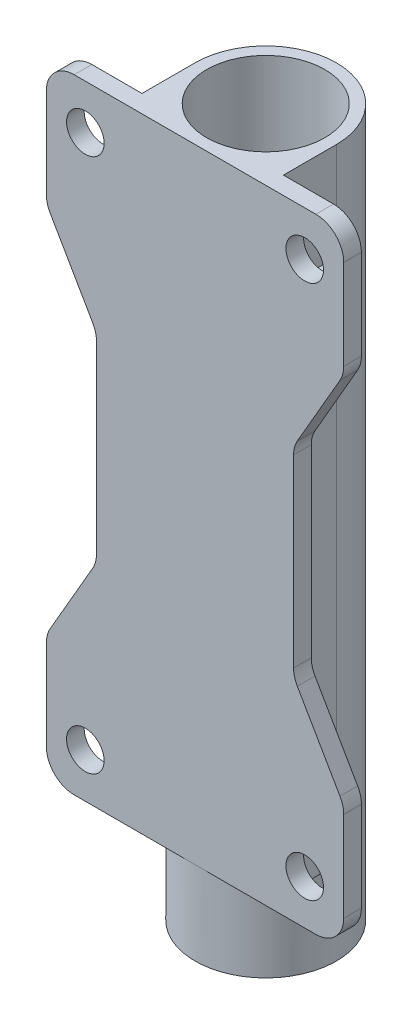
SolidWorks part; units mm, degrees
other "pipe" parameters "D1"=877.6559, "D2"=75.5022, "D3"=726.6514, "D4"=726.6514, "D5"=877.6559, "D6"=4.445, "D7"=9.9955, "\"bearing_bore_min\""=42.164, "D8"=59.5421, "D9"=6.35, "D10"=1.4503
material "6061 Alloy"
ref_plane "Front Plane" through (0, 0, 0) normal (0, 0, 1) x (1, 0, 0)
ref_plane "Top Plane" through (0, 0, 0) normal (0, 1, 0) x (1, 0, 0)
ref_plane "Right Plane" through (0, 0, 0) normal (1, 0, 0) x (0, 0, -1)
sketch "Sketch11" plane through (0, 0, 0) normal (0, 0, 1) x (1, 0, 0)
  line L0 (0, 0) -> (0, 109.6398) construction
  line L1 (0, 0) -> (-89.1372, 0) construction
sketch "Sketch12" plane through (0, 0, 0) normal (0, 0, 1) x (1, 0, 0)
  line L0 (-25.4, 0) -> (-25.4, 254)
  line L1 (200000, 0) -> (-200089.1372, 0) construction
  line L4 (-21.2287, 0) -> (-25.4, 0)
  line L5 (-21.2287, 0) -> (-21.2287, 127)
  line L9 (-21.2287, 127) -> (-21.2287, 254)
  line L10 (-21.2287, 254) -> (-25.4, 254)
  line L13 (-21.2287, 254) -> (0, 254) construction
  line L14 (0, 254) -> (0, 0) construction
  line L15 (0, 0) -> (-21.2287, 0) construction
  point P12 (-25.4, 0)
  dimension "D5" = 254
  dimension "D6" = 4.1713
  dimension "D1" = 50.8
  dimension "D2" = 42.4573
  dimension "D8" = 50.8
  dimension "D9" = 0
revolve "Revolve1" add sketch "Sketch12" angle 360 about L0
ref_plane "mideplane" through (0, 127, 0) normal (0, -1, 0) x (-1, 0, 0)
ref_plane "top pipe plane" through (0, 30, 0) normal (0, -1, 0) x (-1, 0, 0)
ref_plane "bottom pipe plane" through (0, 254, 0) normal (0, 1, 0) x (1, 0, 0)
ref_plane "pipe support midplane" through (0, 142, 0) normal (0, -1, 0) x (-1, 0, 0)
sketch "Sketch14" plane through (0, 30, 0) normal (0, -1, 0) x (-1, 0, 0)
  line L0 (0, 0) -> (-25.4, 0) construction
  line L1 (0, 0) -> (25.4, 0) construction
  line L7 (-25.4, -25.4) -> (25.4, -25.4)
  line L9 (25.4, -25.4) -> (25.4, 0)
  line L10 (-25.4, -25.4) -> (-25.4, 0)
  circle A0 centre (0, 0) radius 25.4 construction
  circle A1 centre (0, 0) radius 25.4
  circle A2 centre (0, 0) radius 25.4 construction
  arc A3 (25.4, 0) -> (-25.4, 0) centre (0, 0) cw
  dimension "D1" = 0
  dimension "D2" = 0
extrude "Boss-Extrude1" add sketch "Sketch14" against normal up to surface (224 mm away) contours A1 L10 L7 L9 | A1 L7 L9
sketch "Sketch27" plane through (0, 0, 25.4) normal (0, 0, 1) x (1, 0, 0)
  line L0 (25.4, 30) -> (53.4, 30)
  line L1 (53.4, 30) -> (53.4, 75)
  line L2 (53.4, 75) -> (35.4, 106.1769)
  line L3 (35.4, 106.1769) -> (35.4, 177.8231)
  line L4 (35.4, 177.8231) -> (53.4, 209)
  line L5 (25.4, 30) -> (25.4, 254)
  line L6 (25.4, 254) -> (-25.4, 254)
  line L7 (-25.4, 254) -> (-25.4, 30)
  line L8 (-25.4, 30) -> (0, 30)
  line L9 (0, 30) -> (25.4, 30)
  line L10 (25.4, 30) -> (25.4, 254) construction
  line L11 (25.4, 254) -> (-25.4, 254)
  line L12 (-25.4, 254) -> (-25.4, 30)
  line L13 (-25.4, 30) -> (0, 30)
  line L14 (0, 30) -> (25.4, 30)
  line L15 (53.4, 209) -> (53.4, 254)
  line L16 (25.4, 254) -> (53.4, 254)
  line L17 (25.4, 254) -> (25.4, 30) construction
  line L18 (25.4, 62) -> (53.4, 30) construction
  line L20 (25.4, 222) -> (53.4, 254) construction
  circle A0 centre (39.4, 46) radius 6 construction
  point P14 (39.4, 238)
  dimension "D2" = 12
  dimension "D3" = 10
  dimension "D6" = 8
  dimension "D4" = 10
  dimension "D5" = 45
  dimension "D7" = 30
  dimension "D1" = 0
extrude "Boss-Extrude2" add sketch "Sketch27" against normal blind 6.35
ref_plane "Plane1" through (0, 65, 0) normal (0, -1, 0) x (-1, 0, 0)
sketch "Sketch32" plane through (0, 65, 0) normal (0, -1, 0) x (-1, 0, 0)
  line L0 (-25.4, -19.05) -> (-53.4, -19.05) construction
  line L1 (-25.4, -19.05) -> (-53.4, -19.05)
  line L3 (-25.4, 0) -> (-25.4, -19.05)
  line L6 (-53.4, -19.05) -> (-25.4, 0)
  arc A0 (25.4, 0) -> (-25.4, 0) centre (0, 0) ccw construction
  arc A1 (25.4, 0) -> (-25.4, 0) centre (0, 0) ccw
extrude "Boss-Extrude3" add sketch "Sketch32" against normal blind 5
mirror "Mirror2" about plane through (0, 142, 0) normal (0, -1, 0) of "Boss-Extrude3"
hole_wizard "M12 Clearance Hole1" positions "Sketch28" profile "Sketch29" hole size "M12" standard "ISO" end condition through all
sketch "Sketch28" plane through (0, 0, 25.4) normal (0, 0, 1) x (1, 0, 0)
  point P0 (39.4, 46)
  point P3 (39.4, 238)
sketch "Sketch29" plane through (39.4, 46, 25.4) normal (1, 0, 0) x (0, -1, 0)
  line L0 (0, 0) -> (0, 50.8)
  line L1 (0, 50.8) -> (6.75, 50.8)
  line L2 (6.75, 50.8) -> (6.75, 0)
  line L5 (6.75, 0) -> (0, 0)
  line L11 (0, -6.35) -> (0, 107.95) construction
  dimension "Thru Hole Dia." = 13.5
  dimension "Thru Hole Depth" = 50.8
fillet "Fillet1" radius 10 6 edges at (53.4, 209, 22.225) (35.4, 177.8231, 22.225) (35.4, 106.1769, 22.225) (53.4, 75, 22.225) (53.4, 254, 22.225) (53.4, 30, 22.225)
mirror "Mirror1" about plane through (0, 0, 0) normal (1, 0, 0) of "Mirror2", "Boss-Extrude2", "M12 Clearance Hole1", "Fillet1", "Boss-Extrude3"
sketch "Sketch35" plane through (0, 0, 0) normal (0, -1, 0) x (1, 0, 0)
  circle A1 centre (0, 0) radius 25.4
  circle A2 centre (0, 0) radius 25.4
  dimension "D1" = 0
extrude "CUT_FOR_PRINT" [suppressed] cut sketch "Sketch35" against normal blind 8
equation "\"bearing_bore\"= 1 + 21 / 32in"
equation "\"bearing_bore_max\"= 1.6568in"
equation "\"bearing_bore_min\"= 1.6558in"
equation "\"shaft_dia\"= 1.5in"
equation "\"shaft_dia_min\"= 1.51in"
equation "\"D2@Sketch12\"=\"bearing_bore_min\"+0.4mm"
equation "\"bearing_flange_diameter\"= 2in"
equation "\"bearing_flange_thickness\"= 0.078in"
equation "\"bearing_length\"= 1.5in"
equation "\"D8@Sketch12\"=\"bearing_flange_diameter\""
equation "\"nub_dia\"= 0.5in"
equation "\"D1@Sketch12\"=2in"
